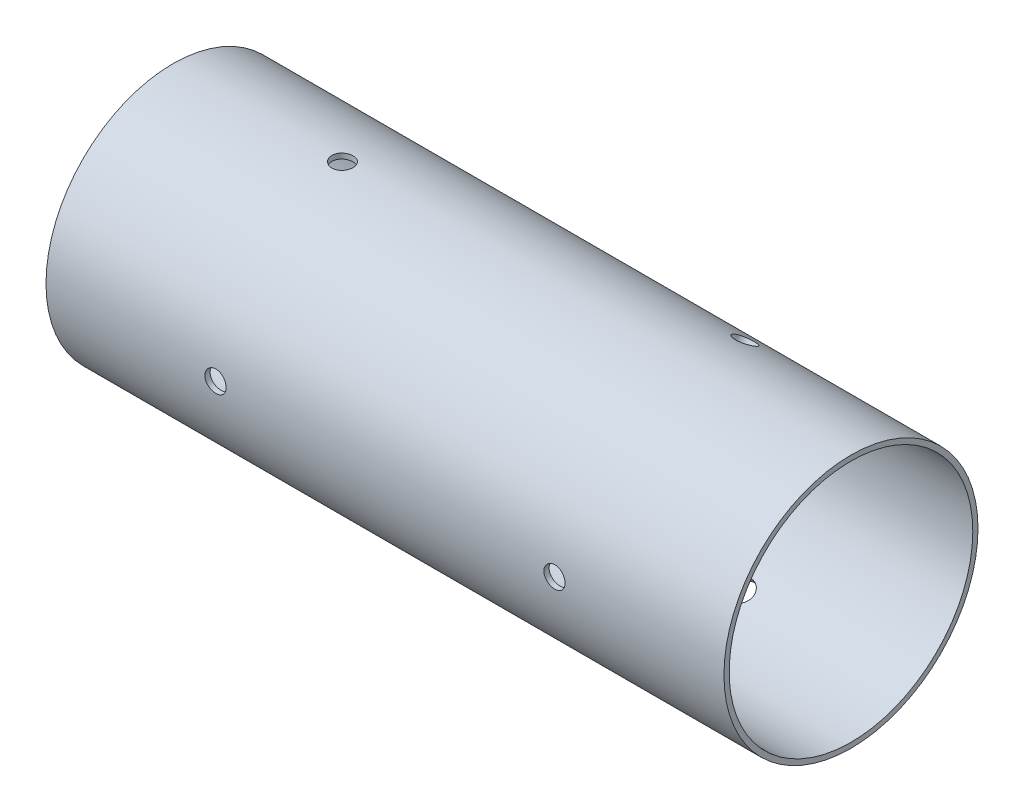
SolidWorks part; units mm, degrees
ref_plane "Front Plane" through (0, 0, 0) normal (1, 0, 0) x (0, 1, 0)
ref_plane "Top Plane" through (0, 0, 0) normal (0, 0, 1) x (0, 1, 0)
ref_plane "Right Plane" through (0, 0, 0) normal (0, 1, 0) x (-1, 0, 0)
sketch "Sketch1" plane through (0, 0, 0) normal (1, 0, 0) x (0, 1, 0)
  circle A0 centre (0, 0) radius 38.0746
  circle A1 centre (0, 0) radius 36.5125
  dimension "D1" = 76.1492
  dimension "D2" = 73.025
extrude "Boss-Extrude1" add sketch "Sketch1" along normal blind 203.2
sketch "Sketch2" plane through (0, 0, 0) normal (0, 1, 0) x (-1, 0, 0)
  circle A0 centre (-50.8, 0) radius 3.175
  dimension "D2" = 6.35
  dimension "D1" = 50.8
extrude "Cut-Extrude1" cut sketch "Sketch2" along normal through all
pattern_circular "CirPattern1" count 4 over 360 about axis through (203.2, 0, 0) along (-1, 0, 0) of "Cut-Extrude1"
ref_plane "Plane2" through (0, 23.8318, 29.6938) normal (0, 0.6259, 0.7799) x (-1, 0, 0)
sketch "Sketch3" plane through (0, 174.2166, 0) normal (0, 0, 1) x (-1, 0, 0)
  line L0 (-203.2, 212.2912) -> (-203.2, 136.142) construction
  circle A0 centre (-152.4, 174.2166) radius 3.175
  dimension "D1" = 6.35
  dimension "D2" = 50.8
extrude "Cut-Extrude2" cut sketch "Sketch3" along normal through all
pattern_circular "CirPattern2" count 3 over 360 about axis through (203.2, 0, 0) along (-1, 0, 0) of "Cut-Extrude2"
